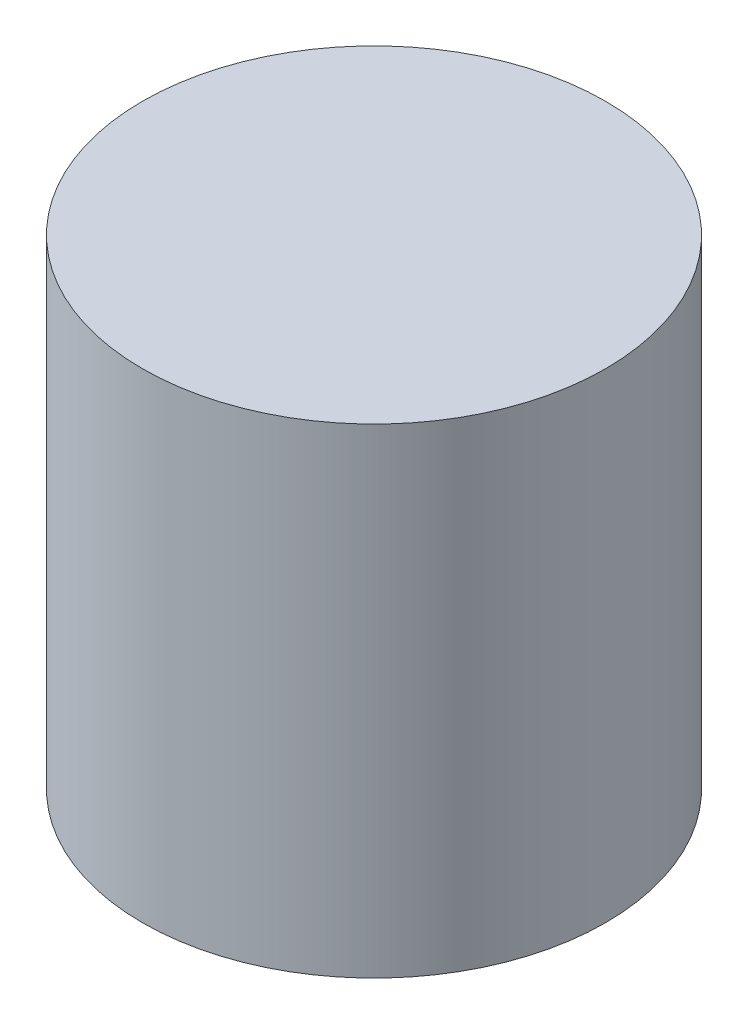
SolidWorks part; units mm, degrees
ref_plane "Front Plane" through (0, 0, 0) normal (0, 0, 1) x (1, 0, 0)
ref_plane "Top Plane" through (0, 0, 0) normal (0, 1, 0) x (1, 0, 0)
ref_plane "Right Plane" through (0, 0, 0) normal (1, 0, 0) x (0, 0, -1)
sketch "Sketch1" plane through (0, 0, 0) normal (0, 1, 0) x (1, 0, 0)
  circle A0 centre (1.0062, 0.7015) radius 34.2724
extrude "Boss-Extrude1" add sketch "Sketch1" along normal blind 71 contours A0
